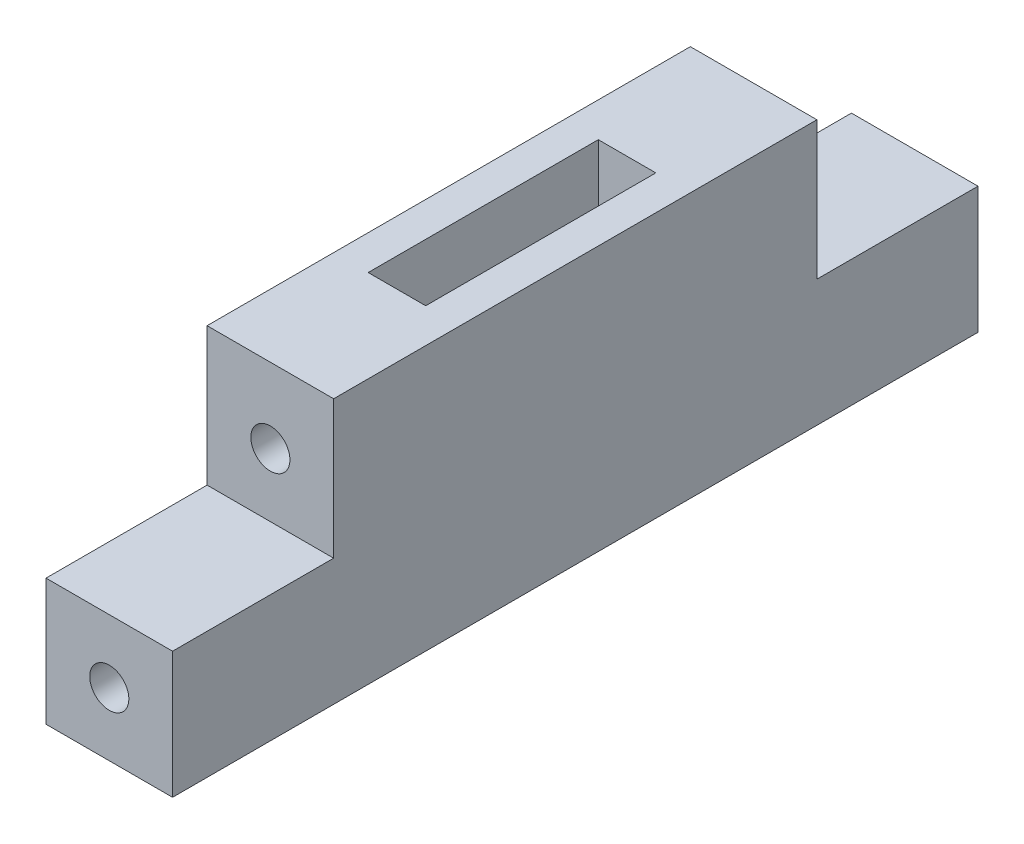
SolidWorks part; units mm, degrees
ref_plane "Front Plane" through (0, 0, 0) normal (0, 0, 1) x (1, 0, 0)
ref_plane "Top Plane" through (0, 0, 0) normal (0, 1, 0) x (1, 0, 0)
ref_plane "Right Plane" through (0, 0, 0) normal (1, 0, 0) x (0, 0, -1)
sketch "Sketch1" plane through (0, 0, 0) normal (0, 0, 1) x (1, 0, 0)
  line L1 (0, 0) -> (11, 0)
  line L2 (0, 0) -> (0, 11)
  line L3 (0, 11) -> (11, 11)
  line L4 (11, 0) -> (11, 11)
  dimension "D1" = 11
  dimension "D2" = 11
extrude "Boss-Extrude1" add sketch "Sketch1" along normal up to surface (70 mm away)
sketch "Sketch2" plane through (0, 11, 0) normal (0, 1, 0) x (1, 0, 0)
  line L0 (0, -70) -> (0, 0) construction
  line L1 (0, -14) -> (11, -14)
  line L2 (0, -14) -> (0, -56)
  line L3 (0, -56) -> (11, -56)
  line L4 (11, -14) -> (11, -56)
  line L5 (11, -70) -> (11, 0) construction
  line L6 (11, 0) -> (0, 0) construction
  line L7 (0, -70) -> (11, -70) construction
  dimension "D1" = 14
  dimension "D2" = 14
extrude "Boss-Extrude2" add sketch "Sketch2" along normal up to surface (12 mm away)
sketch "Sketch3" plane through (0, 23, 0) normal (0, 1, 0) x (1, 0, 0)
  line L0 (-3.175, -25) -> (190, -25) construction
  line L1 (8, -25) -> (3, -25)
  line L2 (8, -25) -> (8, -45)
  line L3 (8, -45) -> (3, -45)
  line L4 (3, -25) -> (3, -45)
  line L5 (-3.175, -45) -> (190, -45) construction
  line L6 (0, -14) -> (0, -56) construction
  dimension "D1" = 5
  dimension "D2" = 3
extrude "Cut-Extrude1" cut sketch "Sketch3" against normal blind 10
sketch "Sketch4" plane through (0, 0, 14) normal (0, 0, -1) x (-1, 0, 0)
  line L0 (0, 23) -> (0, 11) construction
  line L1 (-11, 11) -> (0, 11) construction
  circle A0 centre (-5.5, 16.5) radius 1.7
  dimension "D3" = 3.4
  dimension "D1" = 5.5
  dimension "D2" = 5.5
extrude "Cut-Extrude2" cut sketch "Sketch4" against normal up to surface (42 mm away) up to face at (4.125, 20, 56)
sketch "Sketch5" plane through (0, 0, 0) normal (0, -1, 0) x (1, 0, 0)
  line L0 (11, 70) -> (11, 0) construction
  line L1 (3, 56) -> (8, 56)
  line L2 (3, 56) -> (3, 54)
  line L3 (3, 54) -> (8, 54)
  line L4 (8, 56) -> (8, 54)
  line L5 (11, 70) -> (0, 70) construction
  line L6 (0, 0) -> (11, 0) construction
  line L7 (3, 14) -> (8, 14)
  line L8 (3, 14) -> (3, 16)
  line L9 (3, 16) -> (8, 16)
  line L10 (8, 14) -> (8, 16)
  dimension "D1" = 5
  dimension "D2" = 3
  dimension "D3" = 2
  dimension "D4" = 14
  dimension "D5" = 14
extrude "Cut-Extrude3" cut sketch "Sketch5" against normal blind 8
sketch "Sketch6" plane through (0, 0, 0) normal (0, 0, -1) x (-1, 0, 0)
  line L0 (0, 11) -> (0, 0) construction
  line L1 (0, 0) -> (-11, 0) construction
  circle A0 centre (-5.5, 5.5) radius 1.7
  dimension "D2" = 5.5
  dimension "D3" = 3.4
  dimension "D1" = 5.5
extrude "Cut-Extrude4" cut sketch "Sketch6" against normal offset from surface (17 mm away) 1 up to face at (5.5, 4, 16) offset beyond the face yes
sketch "Sketch7" plane through (0, 0, 70) normal (0, 0, 1) x (1, 0, 0)
  circle A0 centre (5.5719, 5.0498) radius 2.5225
sketch "Sketch8" plane through (0, 0, 70) normal (0, 0, 1) x (1, 0, 0)
  line L0 (0, 0) -> (0, 11) construction
  line L1 (11, 0) -> (0, 0) construction
  circle A0 centre (5.5, 5.5) radius 1.7
  dimension "D1" = 5.5
  dimension "D2" = 5.5
  dimension "D3" = 3.4
extrude "Cut-Extrude5" cut sketch "Sketch8" against normal offset from surface (17 mm away) 1 up to face at (5.5, 4, 54) offset beyond the face yes
